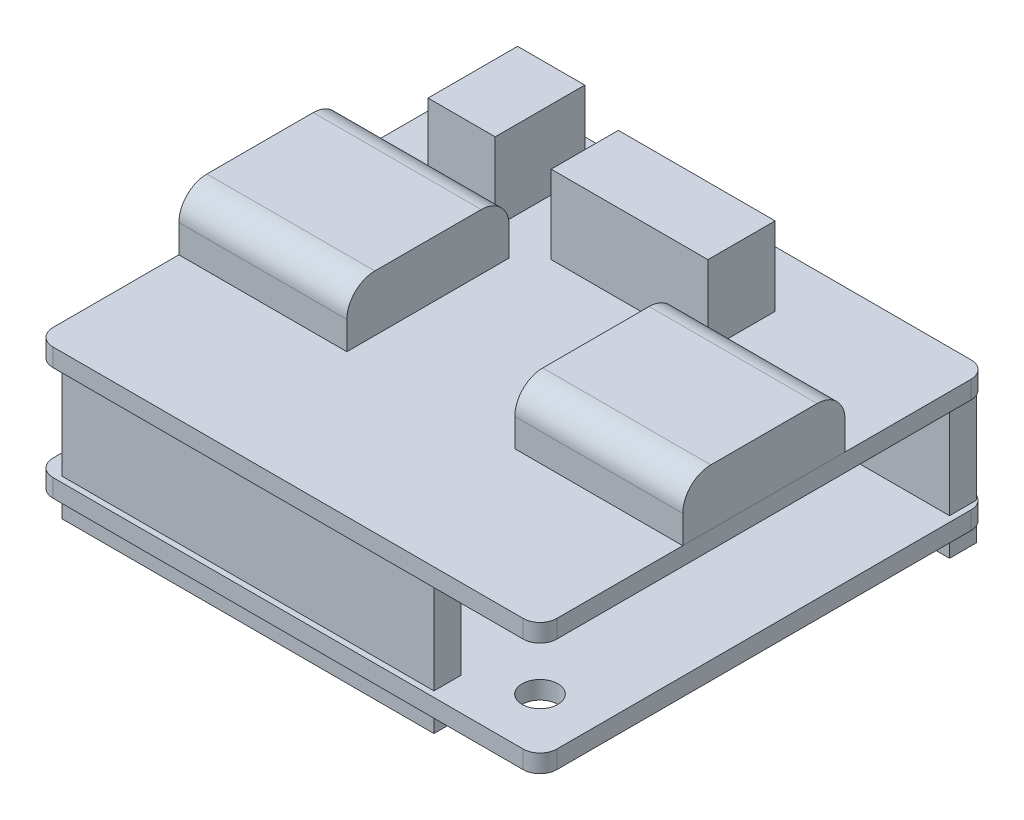
SolidWorks part; units mm, degrees
ref_plane "Front Plane" through (0, 0, 0) normal (0, 0, 1) x (1, 0, 0)
ref_plane "Top Plane" through (0, 0, 0) normal (0, 1, 0) x (1, 0, 0)
ref_plane "Right Plane" through (0, 0, 0) normal (1, 0, 0) x (0, 0, -1)
sketch "Sketch1" plane through (0, 0, 0) normal (0, 1, 0) x (1, 0, 0)
  line L1 (-22.5, -20) -> (22.5, -20)
  line L2 (-22.5, -20) -> (-22.5, 20)
  line L3 (-22.5, 20) -> (22.5, 20)
  line L4 (22.5, -20) -> (22.5, 20)
  line L5 (-22.5, -20) -> (22.5, 20) construction
  line L6 (-22.5, 20) -> (22.5, -20) construction
  point P0 (0, 0)
  dimension "D1" = 45
  dimension "D2" = 40
extrude "Boss-Extrude1" add sketch "Sketch1" along normal blind 1.6
sketch "Sketch2" plane through (0, 1.6, 0) normal (0, 1, 0) x (1, 0, 0)
  line L0 (-21.19, -20) -> (-21.19, 20) construction
  line L1 (21.99, 19.49) -> (-3.92, 19.49)
  line L2 (21.99, 19.49) -> (21.99, 17.08)
  line L3 (21.99, 17.08) -> (-3.92, 17.08)
  line L4 (-3.92, 19.49) -> (-3.92, 17.08)
  line L5 (12.52, -17.08) -> (-20.68, -17.08)
  line L6 (12.52, -17.08) -> (12.52, -19.49)
  line L7 (12.52, -19.49) -> (-20.68, -19.49)
  line L8 (-20.68, -17.08) -> (-20.68, -19.49)
  line L9 (-22.5, -20) -> (22.5, -20) construction
  line L10 (22.5, 20) -> (-22.5, 20) construction
  line L11 (22.5, -20) -> (22.5, 20) construction
  circle A0 centre (17.5, -15) radius 3.2 construction
  dimension "D6" = 6.4
  dimension "D1" = 2.41
  dimension "D2" = 2.41
  dimension "D3" = 33.2
  dimension "D4" = 25.91
  dimension "D5" = 43.69
  dimension "D7" = 5
  dimension "D8" = 5
  dimension "D9" = 0.51
  dimension "D10" = 0.51
  dimension "D11" = 0.51
  dimension "D12" = 0.51
extrude "Boss-Extrude2" add sketch "Sketch2" along normal blind 8.5 and the other way blind 3.3
sketch "Sketch3" plane through (0, 10.1, 0) normal (0, 1, 0) x (1, 0, 0)
  line L0 (22.5, 20) -> (-22.5, 20) construction
  line L1 (22.5, -20) -> (-22.5, -20)
  line L2 (22.5, -20) -> (22.5, 20)
  line L3 (22.5, 20) -> (-22.5, 20)
  line L4 (-22.5, -20) -> (-22.5, 20)
  dimension "D1" = 45
extrude "Boss-Extrude3" add sketch "Sketch3" along normal blind 1.6
sketch "Sketch4" plane through (0, 11.7, 0) normal (0, 1, 0) x (1, 0, 0)
  line L0 (12.52, -17.08) -> (-20.68, -17.08)
  line L1 (12.52, -17.08) -> (12.52, -19.49)
  line L2 (12.52, -19.49) -> (-20.68, -19.49)
  line L3 (-20.68, -17.08) -> (-20.68, -19.49)
  line L4 (-22.5, -20) -> (22.5, -20) construction
  line L5 (22.5, -20) -> (22.5, 20) construction
  dimension "D1" = 0.51
  dimension "D2" = 2.41
  dimension "D3" = 33.2
  dimension "D4" = 9.98
extrude "Boss-Extrude4" [suppressed] add sketch "Sketch4" along normal blind 8.51
sketch "Sketch5" plane through (0, 11.7, 0) normal (0, 1, 0) x (1, 0, 0)
  line L0 (-22.5, 20) -> (-22.5, -20) construction
  line L1 (-22.5, -7.25) -> (-7.5, -7.25)
  line L2 (-22.5, -7.25) -> (-22.5, 7.25)
  line L3 (-22.5, 7.25) -> (-7.5, 7.25)
  line L4 (-7.5, -7.25) -> (-7.5, 7.25)
  line L5 (-0.88, 0) -> (0.88, 0) construction
  point P6 (-7.5, 0)
  dimension "D1" = 14.5
  dimension "D2" = 15
extrude "Boss-Extrude5" add sketch "Sketch5" along normal blind 5 separate body
fillet "Fillet1" radius 2.5 2 edges at (-15, 16.7, -7.25) (-15, 16.7, 7.25)
sketch "Sketch7" plane through (0, 1.6, 0) normal (0, 1, 0) x (1, 0, 0)
  line L0 (-22.5, -20) -> (22.5, -20) construction
  line L1 (22.5, -20) -> (22.5, 20) construction
  line L2 (-22.5, 20) -> (-22.5, -20) construction
  line L3 (22.5, 20) -> (-22.5, 20) construction
  circle A0 centre (17.5, -15) radius 1.6
  circle A1 centre (-17.5, 15) radius 1.6
  dimension "D3" = 3.2
  dimension "D6" = 3.2
  dimension "D1" = 5
  dimension "D2" = 5
  dimension "D4" = 5
  dimension "D5" = 5
extrude "Cut-Extrude1" cut sketch "Sketch7" against normal up to next (1.6 mm away)
fillet "Fillet2" radius 1.5 4 edges at (-22.5, 0.8, -20) (-22.5, 0.8, 20) (22.5, 0.8, 20) (22.5, 0.8, -20)
fillet "Fillet3" radius 1.5 4 edges at (-22.5, 10.9, -20) (22.5, 10.9, 20) (22.5, 10.9, -20) (-22.5, 10.9, 20)
sketch "Sketch8" plane through (0, 11.7, 0) normal (0, 1, 0) x (1, 0, 0)
  line L1 (-5.5, 9) -> (8.5, 9)
  line L2 (-5.5, 9) -> (-5.5, 15)
  line L3 (-5.5, 15) -> (8.5, 15)
  line L4 (8.5, 9) -> (8.5, 15)
  line L5 (21, 20) -> (-21, 20) construction
  line L6 (-22.5, 18.5) -> (-22.5, -18.5) construction
  line L7 (-16.5, 9) -> (-10.5, 9)
  line L8 (-16.5, 9) -> (-16.5, 17)
  line L9 (-16.5, 17) -> (-10.5, 17)
  line L10 (-10.5, 9) -> (-10.5, 17)
  dimension "D1" = 6
  dimension "D2" = 14
  dimension "D3" = 5
  dimension "D4" = 8
  dimension "D5" = 6
  dimension "D6" = 3
  dimension "D7" = 6
  dimension "D8" = 17
extrude "Boss-Extrude6" add sketch "Sketch8" along normal blind 7
pattern_linear "LPattern1" count 2 spacing 30 along (1, 0, 0) of "Boss-Extrude5"
